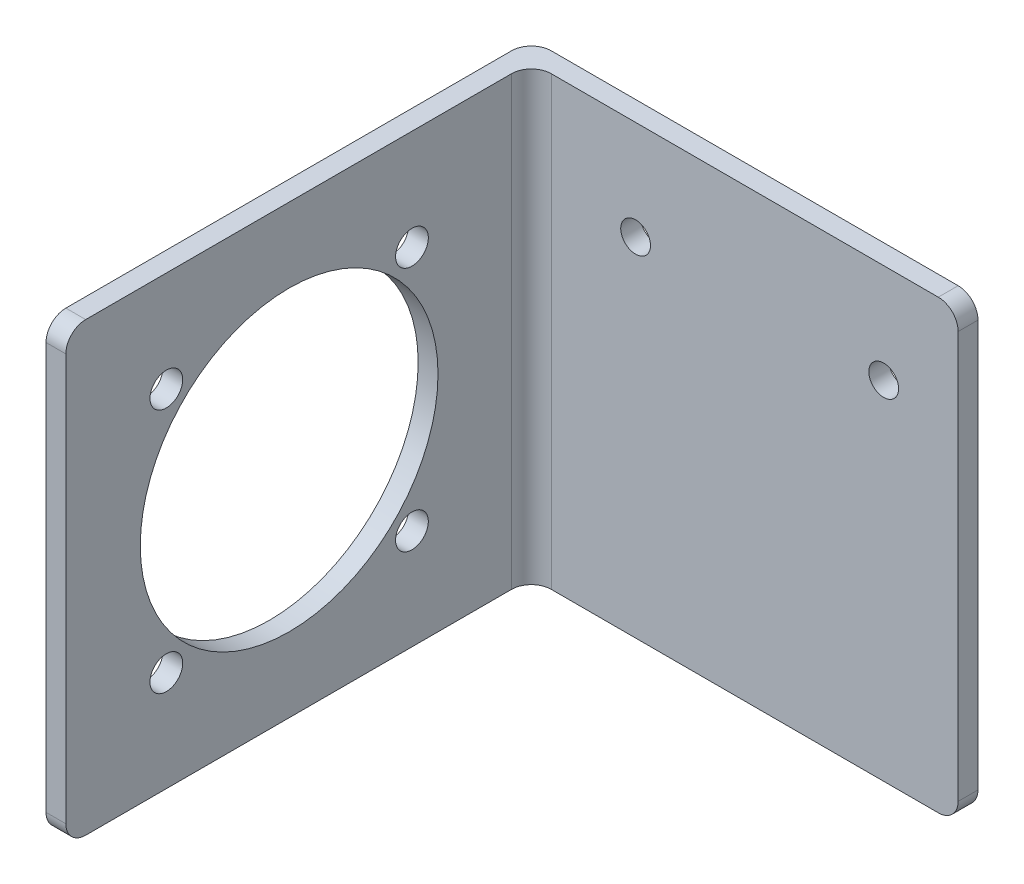
SolidWorks part; units mm, degrees
material "1023 碳钢板 (SS)"
ref_plane "前视基准面" through (0, 0, 0) normal (0, 0, 1) x (1, 0, 0)
ref_plane "上视基准面" through (0, 0, 0) normal (0, 1, 0) x (1, 0, 0)
ref_plane "右视基准面" through (0, 0, 0) normal (1, 0, 0) x (0, 0, -1)
other "Configuration Table"
sketch "草图1" plane through (0, 0, 0) normal (0, 1, 0) x (1, 0, 0)
  line L0 (0, 0) -> (0, 48.91)
  line L1 (0, 48.91) -> (45, 48.91)
  dimension "D1" = 48.91
  dimension "D2" = 45
extrude "拉伸-薄壁1" add sketch "草图1" along normal blind 45 thin
fillet "圆角1" radius 2 2 edges at (2, 22.5, -46.91) (0, 22.5, -48.91)
sketch "草图2" plane through (0, 0, 0) normal (-1, 0, 0) x (0, 0, 1)
  line L0 (0, 0) -> (-46.91, 0) construction
  line L1 (0, 45) -> (0, 0) construction
  circle A0 centre (-22.5, 22.5) radius 15
  dimension "D1" = 30
  dimension "D2" = 22.5
  dimension "D3" = 22.5
extrude "切除-拉伸1" cut sketch "草图2" against normal blind 10
fillet "圆角2" radius 2 4 edges at (45, 0, -47.91) (45, 45, -47.91) (1, 0, 0) (1, 45, 0)
sketch "草图3" plane through (0, 0, 0) normal (-1, 0, 0) x (0, 0, 1)
  circle A0 centre (-22.5, 22.5) radius 17.5 construction
  circle A1 centre (-11.5674, 36.1649) radius 1.7404
  circle A2 centre (-12.103, 8.4234) radius 2.4153
  dimension "D1" = 35
sketch "草图4" plane through (0, 0, 0) normal (-1, 0, 0) x (0, 0, 1)
  circle A1 centre (-34.8744, 10.1256) radius 1.65
  circle A2 centre (-34.8744, 10.1256) radius 1.65
  circle A3 centre (-10.1256, 10.1256) radius 1.65
  circle A4 centre (-10.1256, 10.1256) radius 1.65
  circle A5 centre (-10.1256, 34.8744) radius 1.65
  circle A6 centre (-10.1256, 34.8744) radius 1.65
  circle A7 centre (-34.8744, 34.8744) radius 1.65
  circle A8 centre (-34.8744, 34.8744) radius 1.65
  dimension "D1" = 0
  dimension "D2" = 0
  dimension "D3" = 0
  dimension "D4" = 0
extrude "切除-拉伸2" cut sketch "草图4" against normal blind 10
sketch "草图5" plane through (0, 0, -46.91) normal (0, 0, 1) x (1, 0, 0)
  line L0 (45, 43) -> (45, 2) construction
  line L1 (4, 45) -> (43, 45) construction
  circle A0 centre (12.5, 35) radius 1.5
  circle A1 centre (37.5, 35) radius 1.5
  dimension "D2" = 3
  dimension "D3" = 3
  dimension "D1" = 25
  dimension "D4" = 7.5
  dimension "D5" = 10
  dimension "D6" = 10
extrude "切除-拉伸3" cut sketch "草图5" against normal blind 10
